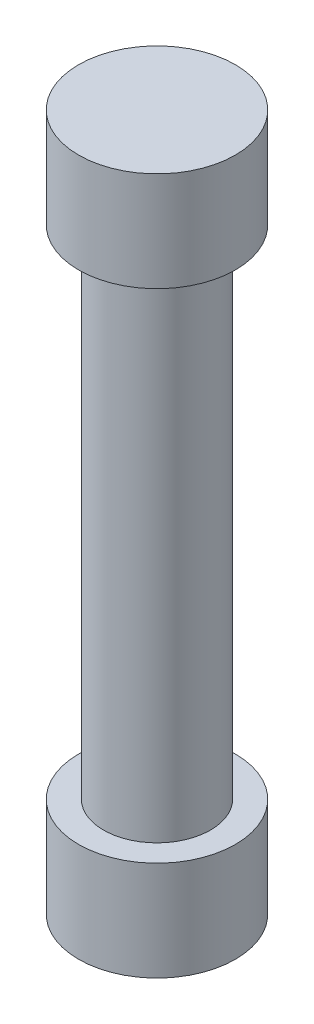
SolidWorks part; units mm, degrees
ref_plane "Front Plane" through (0, 0, 0) normal (0, 0, 1) x (1, 0, 0)
ref_plane "Top Plane" through (0, 0, 0) normal (0, 1, 0) x (1, 0, 0)
ref_plane "Right Plane" through (0, 0, 0) normal (1, 0, 0) x (0, 0, -1)
sketch "Sketch1" plane through (0, 0, 0) normal (0, 0, 1) x (1, 0, 0)
  line L0 (0, 0) -> (0, 28)
  line L1 (0, 28) -> (-3.15, 28)
  line L2 (-3.15, 28) -> (-3.15, 24)
  line L3 (-3.15, 24) -> (-2.15, 24)
  line L4 (-2.15, 24) -> (-2.15, 4)
  line L8 (-3.15, 4) -> (-3.15, 0)
  line L9 (-3.15, 4) -> (-2.15, 4)
  line L10 (-3.15, 0) -> (0, 0)
  dimension "D1" = 28
  dimension "D2" = 4
  dimension "D3" = 3.15
  dimension "D4" = 1
  dimension "D5" = 4
  dimension "D6" = 3.15
revolve "Revolve1" add sketch "Sketch1" angle 360 about L0
